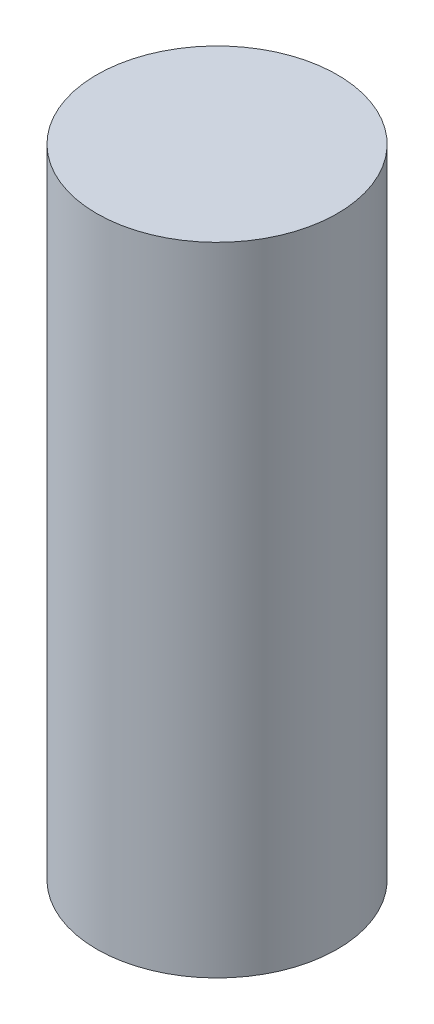
SolidWorks part; units mm, degrees
ref_plane "Ön Düzlem" through (0, 0, 0) normal (0, 0, 1) x (1, 0, 0)
ref_plane "Üst Düzlem" through (0, 0, 0) normal (0, 1, 0) x (1, 0, 0)
ref_plane "Sağ Düzlem" through (0, 0, 0) normal (1, 0, 0) x (0, 0, -1)
sketch "Çizim1" plane through (0, 0, 0) normal (0, 1, 0) x (1, 0, 0)
  circle A0 centre (0, 0) radius 3
  dimension "D1" = 6
extrude "Yükseklik-Ekstrüzyon1" add sketch "Çizim1" along normal blind 15.89
